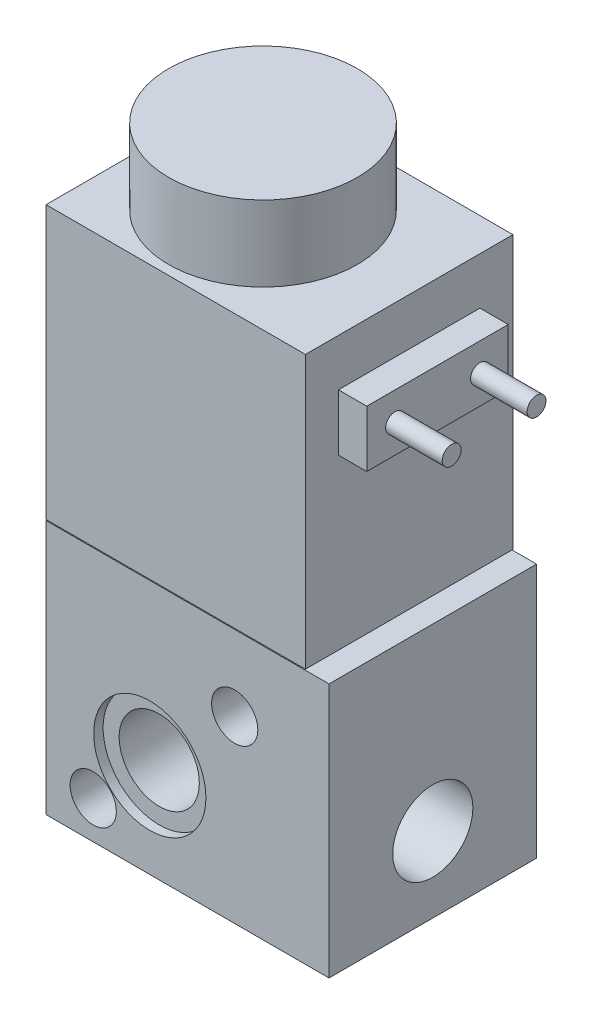
SolidWorks part; units mm, degrees
ref_plane "Plan de face" through (0, 0, 0) normal (0, 0, 1) x (1, 0, 0)
ref_plane "Plan de dessus" through (0, 0, 0) normal (0, 1, 0) x (1, 0, 0)
ref_plane "Plan de droite" through (0, 0, 0) normal (1, 0, 0) x (0, 0, -1)
sketch "Esquisse1" plane through (0, 0, 0) normal (0, 0, 1) x (1, 0, 0)
  line L1 (0, 0) -> (30, 0)
  line L2 (0, 0) -> (0, 27)
  line L3 (0, 27) -> (30, 27)
  line L4 (30, 0) -> (30, 27)
  line L5 (0, 27.1) -> (27.5, 27.1)
  line L6 (0, 27.1) -> (0, 56)
  line L7 (0, 56) -> (27.5, 56)
  line L8 (27.5, 27.1) -> (27.5, 56)
  circle A0 centre (11, 10) radius 4.25
  circle A1 centre (20, 19) radius 1.5
  circle A2 centre (5, 4) radius 1.5
  dimension "D6" = 3
  dimension "D7" = 8.5
  dimension "D8" = 10
  dimension "D9" = 20
  dimension "D10" = 25
  dimension "D11" = 4
  dimension "D13" = 19
  dimension "D14" = 11
  dimension "D15" = 10
  dimension "D1" = 0.1
  dimension "D2" = 30
  dimension "D3" = 27.5
  dimension "D4" = 56
  dimension "D5" = 27
  dimension "D12" = 19
extrude "Boss.-Extru.1" add sketch "Esquisse1" along normal blind 11
sketch "Esquisse2" plane through (0, 0, 11) normal (0, 0, 1) x (1, 0, 0)
  circle A0 centre (20, 19) radius 2.45
  circle A1 centre (5, 4) radius 2.45
  dimension "D1" = 4.9
extrude "Enlèv. mat.-Extru.1" cut sketch "Esquisse2" against normal blind 8
sketch "Esquisse3" plane through (0, 0, 11) normal (0, 0, 1) x (1, 0, 0)
  circle A0 centre (11, 10) radius 5.95
  dimension "D1" = 11.9
extrude "Enlèv. mat.-Extru.2" cut sketch "Esquisse3" against normal blind 1
sketch "Esquisse4" plane through (30, 0, 0) normal (1, 0, 0) x (0, 0, -1)
  line L0 (0, 0) -> (0, 27) construction
  line L1 (-11, 0) -> (0, 0) construction
  circle A0 centre (0, 8) radius 4.25
  dimension "D1" = 8.5
  dimension "D2" = 8
extrude "Enlèv. mat.-Extru.3" cut sketch "Esquisse4" against normal blind 8
sketch "Esquisse5" plane through (27.5, 0, 0) normal (1, 0, 0) x (0, 0, -1)
  line L0 (0, 27.1) -> (0, 56) construction
  line L1 (-7.5, 51) -> (0, 51)
  line L2 (-7.5, 51) -> (-7.5, 45)
  line L3 (-7.5, 45) -> (0, 45)
  line L4 (0, 51) -> (0, 45)
  line L5 (-11, 56) -> (0, 56) construction
  line L6 (-11, 27.1) -> (-11, 56) construction
  dimension "D1" = 6
  dimension "D2" = 5
  dimension "D3" = 3.5
extrude "Boss.-Extru.2" add sketch "Esquisse5" along normal blind 3
sketch "Esquisse6" plane through (30.5, 0, 0) normal (1, 0, 0) x (0, 0, -1)
  line L0 (0, 45) -> (0, 51) construction
  line L1 (-7.5, 51) -> (-7.5, 45) construction
  circle A0 centre (-4.5, 48) radius 1
  point P6 (-7.5, 48)
  dimension "D1" = 2
  dimension "D2" = 4.5
extrude "Boss.-Extru.3" add sketch "Esquisse6" along normal blind 6 separate body
hole_wizard "Trou taraudé M4x0.71" positions "Esquisse8" profile "Esquisse7" tap size "M4x0.7" standard "Ansi Metric"
sketch "Esquisse8" plane through (0, 0, 0) normal (0, -1, 0) x (-1, 0, 0)
  line L0 (0, 0) -> (-30, 0) construction
  line L1 (-30, -11) -> (-30, 0) construction
  point P0 (-25, -7.5)
  dimension "D1" = 7.5
  dimension "D2" = 5
sketch "Esquisse7" plane through (25, 0, 7.5) normal (1, 0, 0) x (0, 0, -1)
  line L0 (0, 0) -> (0, 13.4914)
  line L1 (0, 13.4914) -> (1.65, 12.5)
  line L2 (1.65, 12.5) -> (1.65, 0)
  line L5 (1.65, 0) -> (0, 0)
  line L10 (0, 13.4914) -> (-1.65, 12.5) construction
  line L11 (0, -6.35) -> (0, 107.95) construction
  dimension "Diamètre du trou pour taraudage" = 3.3
  dimension "Profondeur du trou pour taraudage" = 12.5
  dimension "Angle de pointe" = 118
cosmetic thread "Filetage de perçage1"
mirror "Symétrie1" about plane through (0, 0, 0) normal (0, 0, -1) of bodies 106 108
mirror "Symétrie2" about plane through (0, 0, 0) normal (0, 0, 1) of bodies 107
sketch "Esquisse9" plane through (0, 56, 0) normal (0, 1, 0) x (1, 0, 0)
  line L0 (0, -11) -> (0, 11) construction
  circle A0 centre (12, 0) radius 10
  dimension "D1" = 20
  dimension "D2" = 12
extrude "Boss.-Extru.4" add sketch "Esquisse9" along normal blind 8
